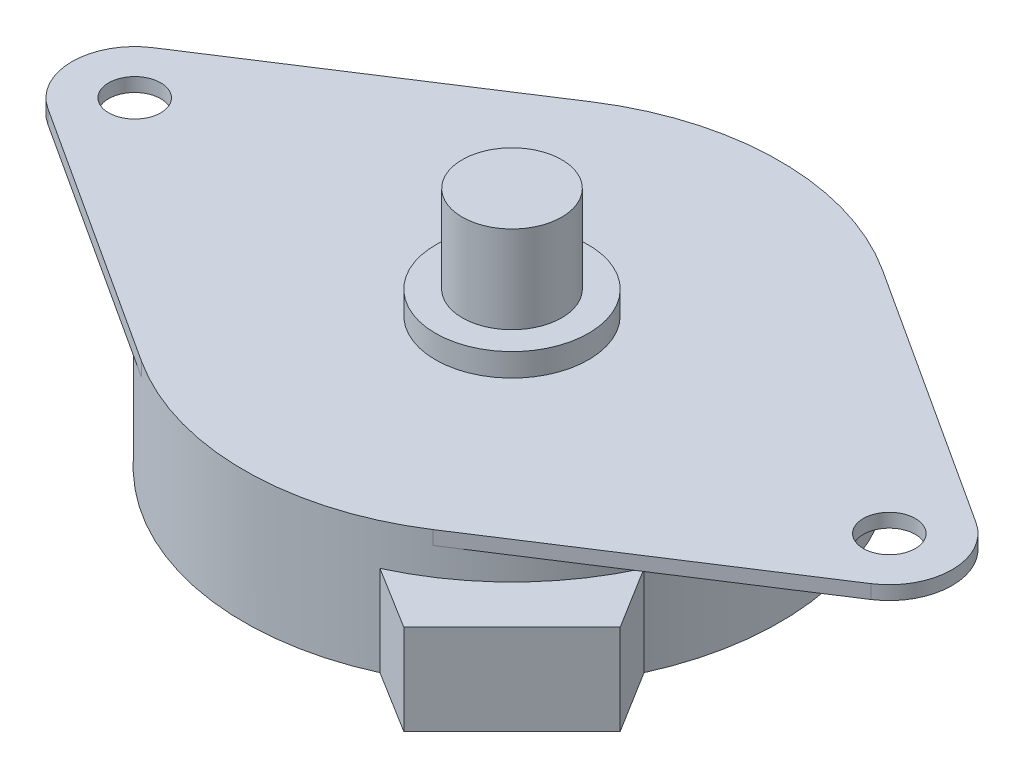
SolidWorks part; units mm, degrees
material "Alloy Steel"
ref_plane "Front Plane" through (0, 0, 0) normal (0, 0, 1) x (1, 0, 0)
ref_plane "Top Plane" through (0, 0, 0) normal (0, 1, 0) x (1, 0, 0)
ref_plane "Right Plane" through (0, 0, 0) normal (1, 0, 0) x (0, 0, -1)
sketch "Sketch1" plane through (0, 0, 0) normal (0, 1, 0) x (1, 0, 0)
  line L0 (0, 17.5) -> (0, -17.5) construction
  line L1 (-26.8788, 3.4413) -> (-9.5132, 14.6884)
  line L2 (-26.8788, -3.4413) -> (-9.5132, -14.6884)
  line L3 (26.8788, -3.4413) -> (9.5132, -14.6884)
  line L4 (26.8788, 3.4413) -> (9.5132, 14.6884)
  circle A0 centre (0, 0) radius 17.5
  circle A1 centre (-24.65, 0) radius 1.7
  circle A2 centre (-24.65, 0) radius 4.1
  circle A3 centre (24.65, 0) radius 1.7
  circle A4 centre (24.65, 0) radius 4.1
  point P7 (-28.75, 0)
  dimension "D1" = 35
  dimension "D2" = 3.4
  dimension "D4" = 28.75
  dimension "D3" = 2.4
extrude "Extrude1" add sketch "Sketch1" along normal blind 0.9 contours A2 L2 A0 L1 | A2 A1 | L0 A0 | A0 L0 | L3 A4 L4 A0 | A4 A3
sketch "Sketch2" plane through (0, 0, 0) normal (0, -1, 0) x (1, 0, 0)
  circle A0 centre (0, 0) radius 17.5
  arc A1 (9.5132, 14.6884) -> (-9.5132, 14.6884) centre (0, 0) ccw construction
extrude "Extrude2" add sketch "Sketch2" along normal blind 7.7
sketch "Sketch3" plane through (0, 0.9, 0) normal (0, 1, 0) x (1, 0, 0)
  circle A0 centre (0, 0) radius 5
  dimension "D1" = 10
extrude "Extrude3" add sketch "Sketch3" along normal blind 1.5
sketch "Sketch4" plane through (0, 2.4, 0) normal (0, 1, 0) x (1, 0, 0)
  circle A0 centre (0, 0) radius 3.25
  dimension "D1" = 6.5
extrude "Extrude4" add sketch "Sketch4" along normal blind 5.7
sketch "Sketch5" plane through (0, -7.7, 0) normal (0, -1, 0) x (1, 0, 0)
  line L0 (7.2849, 15.9116) -> (15.9116, 7.2849)
  line L1 (0, 0) -> (11.5983, 11.5983) construction
  line L2 (0, 0) -> (17.5, 0) construction
  line L3 (11.3861, 18.4572) -> (18.4572, 11.3861)
  line L4 (11.5983, 11.5983) -> (14.9217, 14.9217) construction
  line L5 (18.4572, 11.3861) -> (15.9116, 7.2849)
  line L6 (11.3861, 18.4572) -> (7.2849, 15.9116)
  circle A0 centre (0, 0) radius 17.5 construction
  arc A1 (15.9116, 7.2849) -> (7.2849, 15.9116) centre (0, 0) ccw
  arc A2 (9.5132, -14.6884) -> (9.5132, 14.6884) centre (0, 0) ccw construction
  point P4 (11.5983, 11.5983)
  point P5 (17.5, 0)
  dimension "D1" = 45
  dimension "D2" = 12.2
  dimension "D3" = 4.7
  dimension "D4" = 10
extrude "Extrude5" add sketch "Sketch5" against normal blind 5.9 contours L0 L6 L3 L5
equation "\"D4@Sketch1\" = 57.5/2"
equation "\"D1@Extrude2\"=8.6-0.9"
